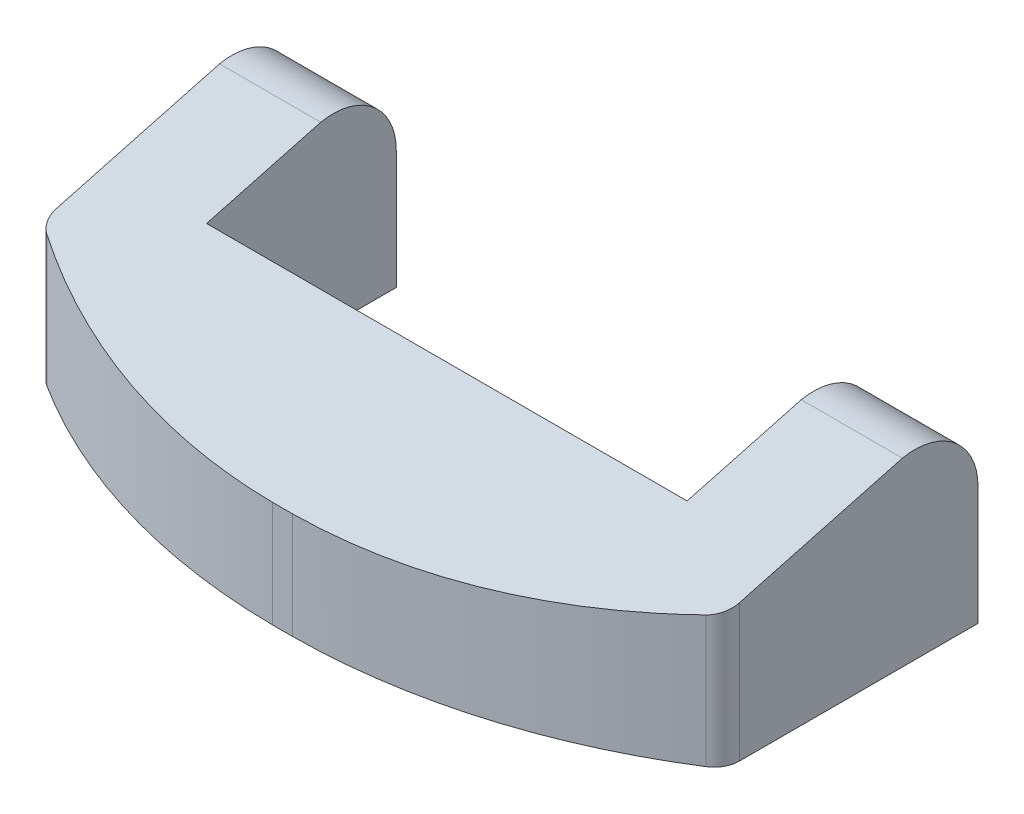
SolidWorks part; units mm, degrees
material "Acrylic (Medium-high impact)"
ref_plane "Front Plane" through (0, 0, 0) normal (0, 0, 1) x (1, 0, 0)
ref_plane "Top Plane" through (0, 0, 0) normal (0, 1, 0) x (1, 0, 0)
ref_plane "Right Plane" through (0, 0, 0) normal (1, 0, 0) x (0, 0, -1)
sketch "Sketch1" plane through (0, 0, 0) normal (0, 1, 0) x (1, 0, 0)
  line L1 (135, 55) -> (-135, 55)
  line L2 (135, 55) -> (135, -55)
  line L3 (135, -55) -> (-135, -55)
  line L4 (-135, 55) -> (-135, -55)
  line L5 (135, 55) -> (-135, -55) construction
  line L6 (135, -55) -> (-135, 55) construction
  point P0 (0, 0)
extrude "Boss-Extrude1" add sketch "Sketch1" along normal blind 70 and the other way blind 2
sketch "Sketch2" plane through (0, 70, 0) normal (0, 1, 0) x (1, 0, 0)
  line L1 (135, 55) -> (-135, 55) construction
  line L2 (-95, 55) -> (-95, -20)
  line L4 (-95, 55) -> (95, 55)
  line L5 (95, -20) -> (0, -20)
  line L6 (0, -20) -> (-95, -20)
  line L7 (95, 55) -> (95, -20)
extrude "Cut-Extrude3" cut sketch "Sketch2" against normal blind 331
sketch "Sketch18" plane through (0, 0, 55) normal (0, 0, 1) x (1, 0, 0)
  line L1 (-135, -2) -> (135, -2)
  line L2 (-135, -2) -> (-135, 70)
  line L3 (-135, 70) -> (135, 70)
  line L4 (135, -2) -> (135, 70)
extrude "Boss-Extrude3" add sketch "Sketch18" along normal blind 30
sketch "Sketch19" plane through (135, 0, 0) normal (1, 0, 0) x (0, 0, -1)
  line L1 (55, 70) -> (55, -2) construction
  line L5 (-85, -2) -> (-85, 70) construction
  line L6 (-85, 40) -> (25.1162, 69.5183)
  arc A0 (55, 45) -> (25.1162, 69.5183) centre (30, 45) ccw
extrude "Cut-Extrude16" cut sketch "Sketch19" against normal through all and the other way through all
sketch "Sketch21" plane through (0, -2, 0) normal (0, -1, 0) x (1, 0, 0)
  line L0 (135, 85) -> (135, 44.7701) construction
  line L1 (135, 85) -> (135, -55) construction
  line L2 (-135, 85) -> (135, 85) construction
  line L3 (0, 85) -> (0, 61.1074) construction
  arc A0 (130.3488, 47.7904) -> (0, 85) centre (1.9769, -154.9919) ccw
  arc A1 (-130.3488, 47.7904) -> (0, 85) centre (-1.9769, -154.9919) cw
  arc A2 (130.3488, 47.7904) -> (135, 39.3411) centre (125, 39.3411) cw
  arc A3 (-135, 39.3411) -> (-130.3488, 47.7904) centre (-125, 39.3411) cw
  point P5 (0, 85)
  point P23 (-135, 44.7701)
  dimension "D1" = 10
extrude "Cut-Extrude17" cut sketch "Sketch21" against normal through all and the other way through all
